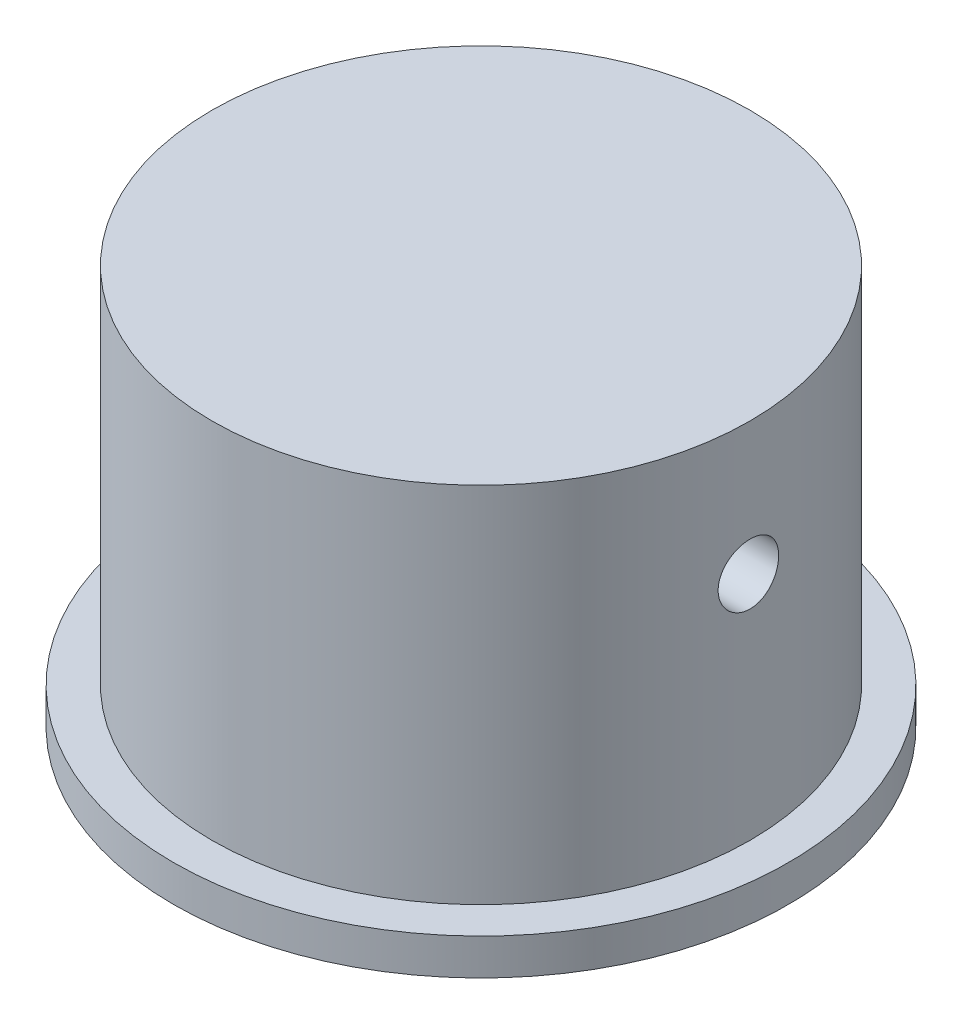
SolidWorks part; units mm, degrees
material "6061 Alloy"
ref_plane "Front Plane" through (0, 0, 0) normal (0, 0, 1) x (1, 0, 0)
ref_plane "Top Plane" through (0, 0, 0) normal (0, 1, 0) x (1, 0, 0)
ref_plane "Right Plane" through (0, 0, 0) normal (1, 0, 0) x (0, 0, -1)
sketch "Sketch1" plane through (0, 0, 0) normal (1, 0, 0) x (0, 0, -1)
  line L3 (-12.7, 0) -> (-12.7, 1.5)
  line L4 (-12.7, 1.5) -> (-11.1125, 1.5)
  line L5 (-11.1125, 1.5) -> (-11.1125, 16.5)
  line L6 (-11.1125, 16.5) -> (0, 16.5)
  line L9 (0, 16.5) -> (0, 5)
  line L10 (0, -1000) -> (0, 49000) construction
  line L11 (-12.7, 0) -> (-2.8067, 0)
  line L12 (-2.8067, 0) -> (-2.8067, 5)
  line L13 (-2.8067, 5) -> (0, 5)
  dimension "D1" = 12.7
  dimension "D2" = 11.1125
  dimension "D3" = 5
  dimension "D4" = 15
  dimension "D5" = 0
  dimension "D6" = 2.8067
  dimension "D7" = 1.5
revolve "Revolve1" add sketch "Sketch1" angle 360 about L10
ref_plane "Plane1" through (11.1125, 0, 0) normal (1, 0, 0) x (0, 0, -1)
hole_wizard "M3x0.5 Tapped Hole1" positions "Sketch2" profile "Sketch4" tap size "M3x0.5" standard "ANSI Metric"
sketch "Sketch2" plane through (11.1125, 0, 0) normal (1, 0, 0) x (0, 0, -1)
  line L0 (12.7, 1.5) -> (-12.7, 1.5) construction
  point P0 (0, 11.025)
  dimension "D1" = 9.525
sketch "Sketch4" plane through (11.1125, 11.025, 0) normal (0, 1, 0) x (0, 0, -1)
  line L0 (0, 0) -> (0, 10.7511)
  line L1 (0, 10.7511) -> (1.25, 10)
  line L2 (1.25, 10) -> (1.25, 0)
  line L5 (1.25, 0) -> (0, 0)
  line L10 (0, 10.7511) -> (-1.25, 10) construction
  line L11 (0, -6.35) -> (0, 107.95) construction
  dimension "Tap Drill Dia." = 2.5
  dimension "Tap Drill Depth" = 10
  dimension "Drill Angle" = 118
cosmetic thread "Hole Thread1" parameters "D1"=6, "D2"=3
mirror "Mirror1" about plane through (0, 0, 0) normal (1, 0, 0) of "M3x0.5 Tapped Hole1"
cosmetic thread "Hole Thread2"
